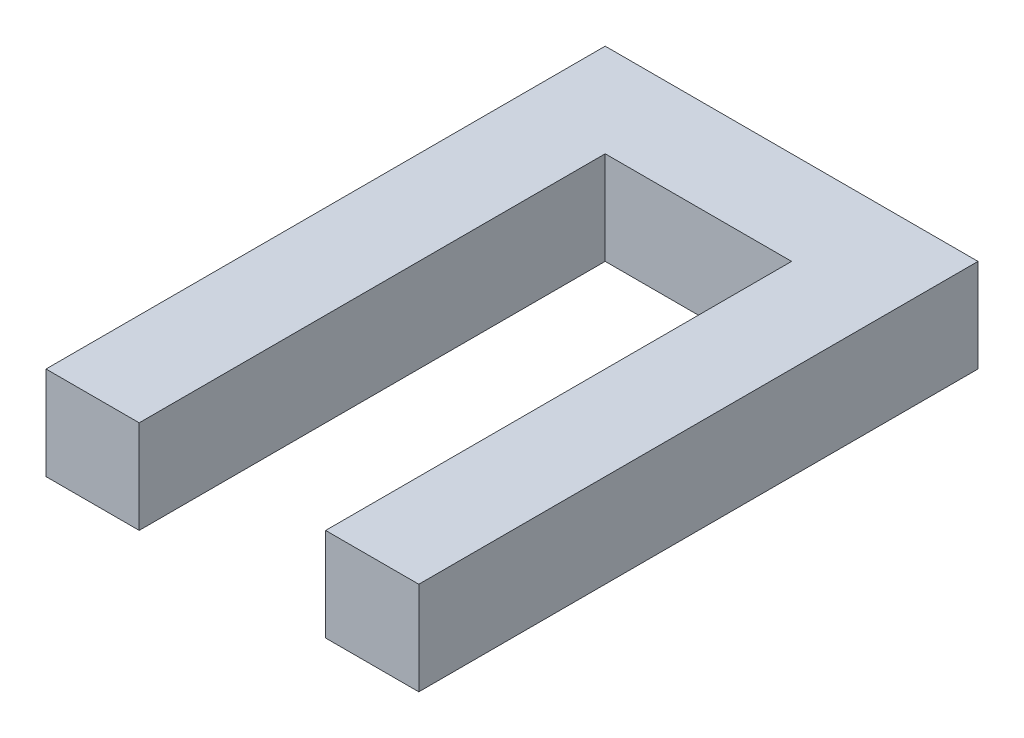
SolidWorks part; units mm, degrees
material "ASTM A36 Steel"
ref_plane "Front Plane" through (0, 0, 0) normal (0, 0, 1) x (1, 0, 0)
ref_plane "Top Plane" through (0, 0, 0) normal (0, 1, 0) x (1, 0, 0)
ref_plane "Right Plane" through (0, 0, 0) normal (1, 0, 0) x (0, 0, -1)
sketch "Sketch1" plane through (0, 0, 0) normal (0, 1, 0) x (1, 0, 0)
  line L0 (2, 4) -> (2, -6)
  line L1 (-2, 4) -> (2, 4)
  line L2 (-2, 4) -> (-2, -6)
  line L3 (4, 6) -> (4, -6)
  line L4 (-4, 6) -> (4, 6)
  line L5 (-4, 6) -> (-4, -6)
  line L6 (-4, -6) -> (-2, -6)
  line L7 (2, -6) -> (4, -6)
extrude "Boss-Extrude1" add sketch "Sketch1" along normal blind 2
sketch "Sketch3" plane through (0, 2, 0) normal (0, 1, 0) x (1, 0, 0)
  line L8 (-2, 4) -> (2, 4)
  line L9 (2, 4) -> (2, -6)
  line L10 (2, -6) -> (4, -6)
  line L11 (4, -6) -> (4, 6)
  line L12 (4, 6) -> (-4, 6)
  line L13 (-4, 6) -> (-4, -6)
  line L14 (-4, -6) -> (-2, -6)
  line L15 (-2, -6) -> (-2, 4)
  line L16 (-2, 4) -> (2, 4)
  line L17 (2, 4) -> (2, -6)
  line L18 (2, -6) -> (4, -6)
  line L19 (4, -6) -> (4, 6)
  line L20 (4, 6) -> (-4, 6)
  line L21 (-4, 6) -> (-4, -6)
  line L22 (-4, -6) -> (-2, -6)
  line L23 (-2, -6) -> (-2, 4)
  dimension "D2" = 12
  dimension "D1" = 0
sketch "Sketch4" plane through (0, 0, 6) normal (0, 0, 1) x (1, 0, 0)
  line L4 (-4, 0) -> (-2, 0)
  line L5 (-2, 0) -> (-2, 2)
  line L6 (-2, 2) -> (-4, 2)
  line L7 (-4, 2) -> (-4, 0)
  line L8 (-4, 0) -> (-2, 0)
  line L9 (-2, 0) -> (-2, 2)
  line L10 (-2, 2) -> (-4, 2)
  line L11 (-4, 2) -> (-4, 0)
  dimension "D1" = 0
sketch "Sketch5" plane through (-4, 0, 0) normal (-1, 0, 0) x (0, 0, 1)
  line L4 (-6, 0) -> (6, 0)
  line L5 (6, 0) -> (6, 2)
  line L6 (6, 2) -> (-6, 2)
  line L7 (-6, 2) -> (-6, 0)
  line L8 (-6, 0) -> (6, 0)
  line L9 (6, 0) -> (6, 2)
  line L10 (6, 2) -> (-6, 2)
  line L11 (-6, 2) -> (-6, 0)
  dimension "D2" = 12
  dimension "D1" = 0
